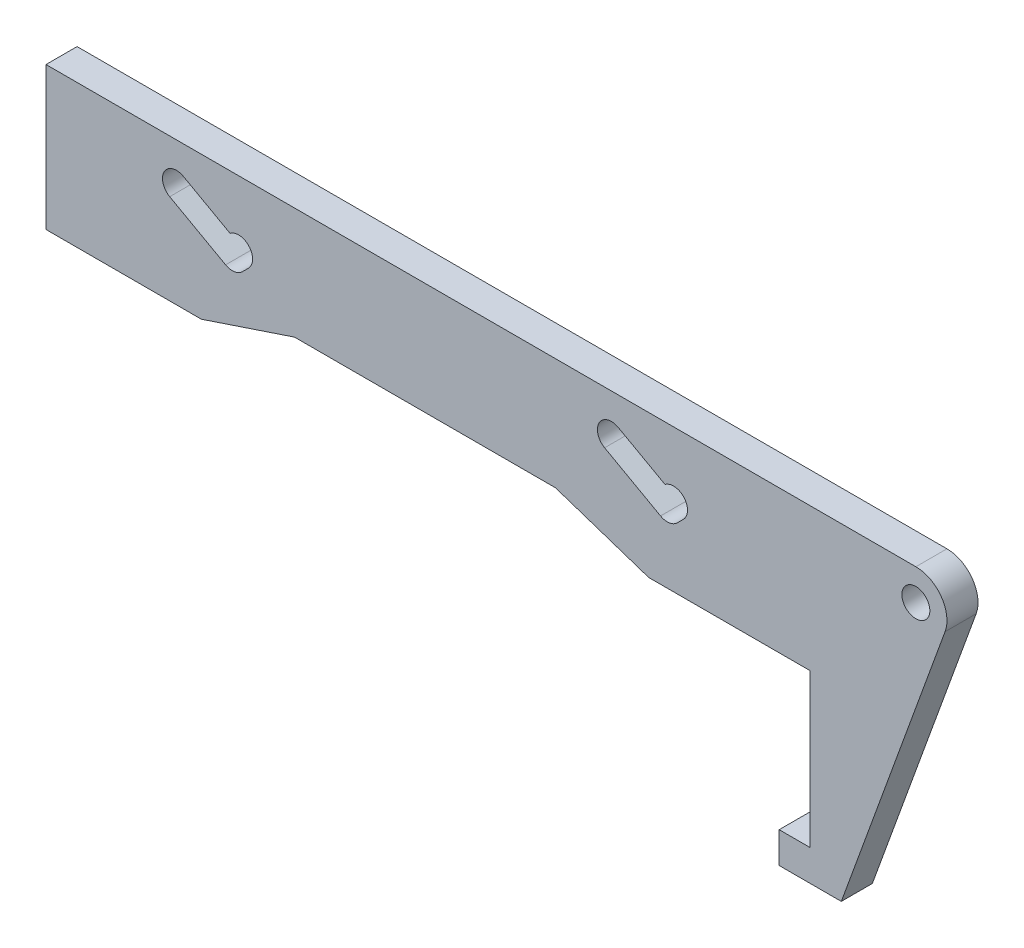
SolidWorks part; units mm, degrees
ref_plane "Front Plane" through (0, 0, 0) normal (0, 0, 1) x (1, 0, 0)
ref_plane "Top Plane" through (0, 0, 0) normal (0, 1, 0) x (1, 0, 0)
ref_plane "Right Plane" through (0, 0, 0) normal (1, 0, 0) x (0, 0, -1)
sketch "Sketch1" plane through (0, 0, 0) normal (0, 0, 1) x (1, 0, 0)
  line L0 (-45, 14) -> (45, 14)
  line L1 (61, -9) -> (-61, -9)
  line L2 (61, -9) -> (61, 9)
  line L3 (61, 9) -> (-61, 9)
  line L4 (-61, -9) -> (-61, 9)
  line L5 (61, -9) -> (-61, 9) construction
  line L6 (61, 9) -> (-61, -9) construction
  line L7 (-45, 14) -> (-45, 9)
  line L8 (45, 14) -> (45, 9)
  line L9 (-32.0927, 0.5331) -> (-41.0927, 5.5331)
  line L10 (-38.9073, 9.4669) -> (-29.9073, 4.4669)
  line L11 (-28.409, 1.909) -> (-29.409, 0.909)
  line L12 (-32.5734, 4.1083) -> (-31.374, 5.2817)
  line L13 (28.9073, 5.5331) -> (37.9073, 0.5331)
  line L14 (31.0927, 9.4669) -> (40.0927, 4.4669)
  line L15 (40.591, 0.909) -> (41.591, 1.909)
  line L16 (37.409, 4.091) -> (38.409, 5.091)
  line L17 (-61, 9) -> (-61, 14)
  line L18 (-61, 14) -> (-45, 14)
  line L19 (61, 9) -> (61, 14)
  line L20 (61, 14) -> (45, 14)
  circle A0 centre (-40, 7.5) radius 2.25
  circle A1 centre (30, 7.5) radius 2.25
  circle A2 centre (-31, 2.5) radius 2.25
  circle A3 centre (39, 2.5) radius 2.25
  circle A4 centre (-30, 3.5) radius 2.25
  circle A5 centre (40, 3.5) radius 2.25
  point P0 (0, 0)
  dimension "D5" = 4.5
  dimension "D6" = 4.5
  dimension "D9" = 4.5
  dimension "D10" = 4.5
  dimension "D13" = 4.5
  dimension "D14" = 4.5
  dimension "D2" = 18
  dimension "D3" = 23
  dimension "D4" = 0
  dimension "D7" = 70
  dimension "D8" = 0
  dimension "D11" = 70
  dimension "D12" = 0
  dimension "D15" = 70
  dimension "D16" = 9
  dimension "D17" = 1
  dimension "D18" = 5
  dimension "D19" = 1
  dimension "D20" = 21
  dimension "D21" = 21
  dimension "D22" = 6.5
  dimension "D23" = 16
  dimension "D24" = 16
extrude "Boss-Extrude1" add sketch "Sketch1" along normal blind 5 contours A5 L15 A3 L13 A1 L3 L10 A4 L11 A2 L9 A0 L4 L1 L2 L14 | A1 L14 L3 L8 L0 L7 A0 L10 | L18 L17 L3 L7 | L19 L20 L8 L3
sketch "Sketch2" plane through (0, 0, 5) normal (0, 0, 1) x (1, 0, 0)
  line L0 (61, -9) -> (-61, -9) construction
  line L1 (-21, -9) -> (21, -9)
  line L2 (-21, -9) -> (-21, -4)
  line L3 (-21, -4) -> (21, -4)
  line L4 (21, -9) -> (21, -4)
  line L5 (-61, -9) -> (-61, 14) construction
  line L6 (61, -9) -> (61, 14) construction
  line L7 (-21, -4) -> (-36, -9)
  line L8 (21, -4) -> (36, -9)
  line M14 (-61, -9) -> (61, -9)
  dimension "D1" = 40
  dimension "D2" = 40
  dimension "D3" = 5
  dimension "D4" = 15
  dimension "D5" = 15
extrude "Cut-Extrude1" cut sketch "Sketch2" against normal blind 5 contours L2 L7 M14 | L4 L3 L2 M14 | L8 L4 M14
sketch "Sketch3" plane through (0, 0, 5) normal (0, 0, 1) x (1, 0, 0)
  line L0 (61, 14) -> (79, 14)
  line L3 (57, -38.65) -> (57, -33.65)
  line L4 (57, -33.65) -> (62, -33.65)
  line L5 (62, -33.65) -> (62, -9)
  line L6 (62, -9) -> (61, -9)
  line L7 (61, -9) -> (61, 14) construction
  line L8 (61, -9) -> (36, -9) construction
  line L9 (61, -9) -> (61, 14)
  line L10 (57, -38.65) -> (67, -38.65)
  line L11 (61, 14) -> (-61, 14) construction
  line L12 (67, -38.65) -> (83.6992, 7.2919)
  circle A0 centre (79, 9) radius 2.25
  circle A2 centre (79, 9) radius 5
  line M10 (61, -9) -> (61, 14)
  dimension "D7" = 4.5
  dimension "D10" = 10
  dimension "D1" = 5
  dimension "D2" = 1
  dimension "D3" = 0
  dimension "D4" = 5
  dimension "D5" = 18
  dimension "D6" = 47.65
  dimension "D8" = 5
  dimension "D9" = 5
extrude "Boss-Extrude2" add sketch "Sketch3" against normal blind 5 contours A2 A0 | A2 L0 L6 L5 L4 L3 L10 L12 M10
